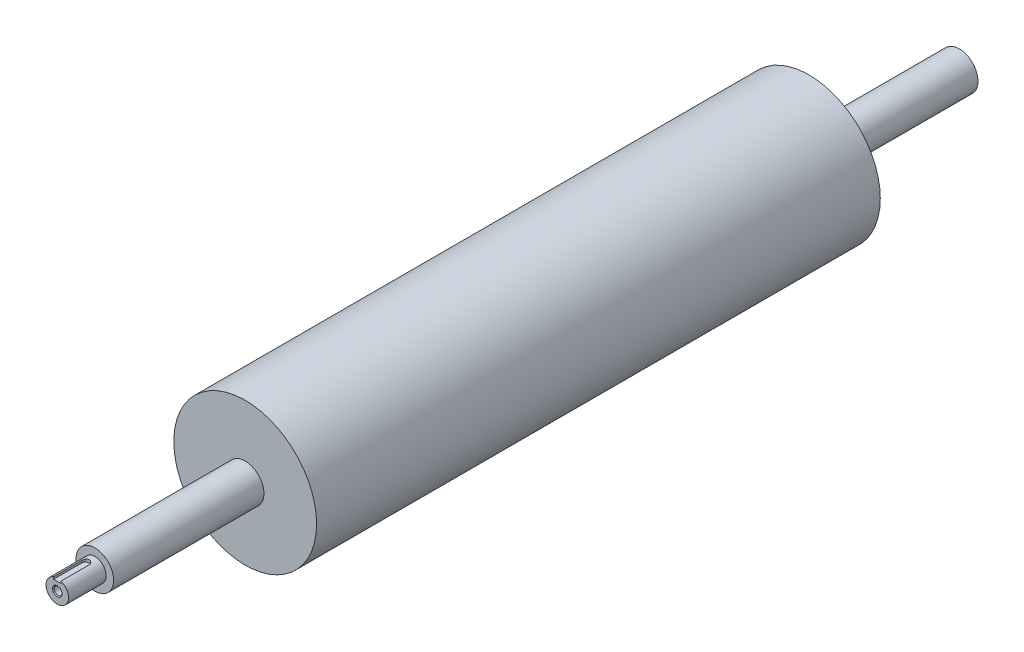
SolidWorks part; units mm, degrees
material "45"
ref_plane "前视基准面" through (0, 0, 0) normal (0, 0, 1) x (1, 0, 0)
ref_plane "上视基准面" through (0, 0, 0) normal (0, 1, 0) x (1, 0, 0)
ref_plane "右视基准面" through (0, 0, 0) normal (1, 0, 0) x (0, 0, -1)
other "Configuration Table"
sketch "草图1" plane through (0, 0, 0) normal (0, 0, 1) x (1, 0, 0)
  circle A0 centre (0, 0) radius 38
  dimension "D1" = 76
extrude "凸台-拉伸1" add sketch "草图1" along normal mid plane 300
sketch "草图2" plane through (0, 0, 150) normal (0, 0, 1) x (1, 0, 0)
  circle A0 centre (0, 0) radius 10
  dimension "D1" = 20
extrude "凸台-拉伸2" add sketch "草图2" along normal blind 80
ref_plane "基准面1" through (0, 0, 0) normal (0, 0, 1) x (1, 0, 0)
mirror "镜向1" about plane through (0, 0, 0) normal (0, 0, 1) of "凸台-拉伸2"
sketch "草图3" plane through (0, 0, 230) normal (0, 0, 1) x (1, 0, 0)
  circle A0 centre (0, 0) radius 6
  dimension "D1" = 12
extrude "凸台-拉伸3" add sketch "草图3" along normal blind 20
sketch "草图4" plane through (0, 0, 0) normal (0, 1, 0) x (1, 0, 0)
  line L0 (0, -250) -> (0, -235) construction
  line L1 (-6, -250) -> (6, -250) construction
  line L2 (-2, -250) -> (-2, -235)
  line L3 (2, -250) -> (2, -235)
  arc A0 (-2, -250) -> (2, -250) centre (0, -250) ccw
  arc A1 (2, -235) -> (-2, -235) centre (0, -235) ccw
  point P5 (0, -242.5)
  dimension "D1" = 4
  dimension "D2" = 15
extrude "切除-拉伸1" cut sketch "草图4" against normal blind 3 from offset 7.5
hole_wizard "M5 螺纹孔1" positions "草图5" profile "草图6" tap size "M5" standard "GB"
sketch "草图5" plane through (0, 0, 250) normal (0, 0, 1) x (1, 0, 0)
  point P0 (0, 0)
cosmetic thread "孔螺纹线1"
sketch "草图6" plane through (0, 0, 250) normal (1, 0, 0) x (0, -1, 0)
  line L0 (0, 0) -> (0, 13.6618)
  line L1 (0, 13.6618) -> (2.1, 12.4)
  line L2 (2.1, 12.4) -> (2.1, 0.425)
  line L3 (2.1, 0.425) -> (2.525, 0)
  line L5 (2.525, 0) -> (0, 0)
  line L6 (-2.1, 0.425) -> (-2.525, 0) construction
  line L10 (0, 13.6618) -> (-2.1, 12.4) construction
  line L11 (0, -6.35) -> (0, 107.95) construction
  dimension "螺纹孔钻头直径" = 4.2
  dimension "螺纹孔钻头深度" = 12.4
  dimension "近端锥形沉头孔直径" = 5.05
  dimension "近端锥形沉头孔角度" = 90
  dimension "导头角度" = 118
